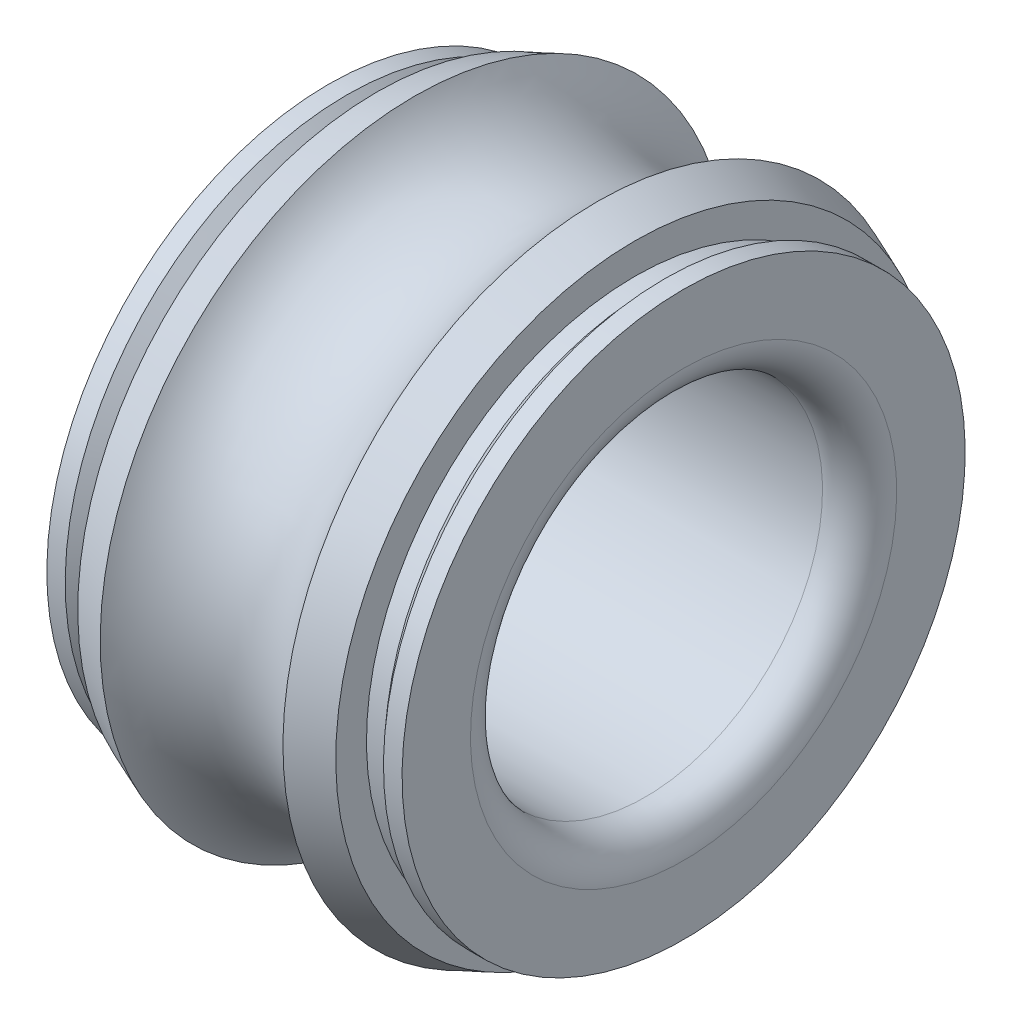
SolidWorks part; units mm, degrees
material "AISI 304"
ref_plane "Plano frontal" through (0, 0, 0) normal (0, 0, 1) x (1, 0, 0)
ref_plane "Plano superior" through (0, 0, 0) normal (0, 1, 0) x (1, 0, 0)
ref_plane "Plano direito" through (0, 0, 0) normal (1, 0, 0) x (0, 0, -1)
sketch "Esboço1" plane through (0, 0, 0) normal (0, 0, 1) x (1, 0, 0)
  line L0 (-22.7175, 2.9568) -> (-17.7175, 2.9568) construction
  line L2 (-1.9877, 2.5015) -> (1.957, 2.5015)
  line L3 (-2.4969, 3.0019) -> (-2.4969, 3.9651)
  line L4 (-1.9705, 8.0015) -> (1.9743, 8.0015)
  line L5 (2.5, 3.0019) -> (2.5, 3.9651)
  line L7 (-2.5, 6.5408) -> (-2.1334, 6.5408)
  line L8 (-1.6236, 6.5408) -> (-1.6236, 6.1298)
  line L9 (-1.6236, 6.1298) -> (-1.1769, 6.1298)
  line L10 (1.6236, 6.1298) -> (1.1769, 6.1298)
  line L11 (1.6236, 6.5408) -> (1.6236, 6.1298)
  line L12 (2.5, 6.5408) -> (2.1334, 6.5408)
  line L13 (-2.1884, 4.1901) -> (-2.1884, 6.0268)
  line L14 (-2.1184, 6.0968) -> (-1.7245, 6.0968)
  line L15 (-1.6545, 6.1668) -> (-1.6545, 6.4667)
  line L16 (-2.1145, 6.4667) -> (-2.1145, 6.3275)
  line L17 (-2.078, 6.2794) -> (-1.8845, 6.2794)
  line L18 (-1.8845, 6.2794) -> (-1.8845, 6.3794)
  line L19 (-1.8845, 6.3794) -> (-1.9445, 6.3794)
  line L20 (-2.0145, 6.4494) -> (-2.0145, 6.4667)
  line L21 (-1.7545, 6.4667) -> (-1.7545, 6.2668)
  line L22 (-1.8245, 6.1968) -> (-2.2192, 6.1968)
  line L23 (-2.1188, 4.1201) -> (-1.9112, 4.1201)
  line L24 (-1.9112, 4.1201) -> (-1.9112, 4.0201)
  line L25 (-1.9112, 4.0201) -> (-2.2184, 4.0201)
  line L26 (-2.2884, 4.0901) -> (-2.2884, 6.0268)
  line L27 (-2.2884, 6.0268) -> (-2.2884, 6.1371)
  line L28 (-2.5, 6.5408) -> (-2.5, 7.5)
  line L29 (2.5, 6.5408) -> (2.5, 7.5)
  line L30 (-2.4969, 3.9651) -> (-2.2384, 3.9651)
  line L31 (-2.2384, 3.9651) -> (-2.0732, 3.7803)
  line L32 (-2.0732, 3.7803) -> (-1.8146, 3.7803)
  line L33 (-1.8146, 3.7803) -> (-1.8146, 4.2124)
  line L34 (-1.8146, 4.2124) -> (-1.2851, 4.4263)
  line L35 (1.8146, 4.2124) -> (1.2851, 4.4263)
  line L36 (1.8146, 3.7803) -> (1.8146, 4.2124)
  line L37 (2.0732, 3.7803) -> (1.8146, 3.7803)
  line L38 (2.2384, 3.9651) -> (2.0732, 3.7803)
  line L39 (2.5, 3.9651) -> (2.2384, 3.9651)
  line L40 (0, 0.0015) -> (-3.7152, 0) construction
  line L41 (0, 0.0015) -> (0, 8) construction
  arc A0 (-2.1334, 6.5408) -> (-1.6236, 6.5408) centre (-1.8785, 6.5408) cw
  arc A1 (-1.2851, 4.4263) -> (1.2851, 4.4263) centre (0, 5.1999) ccw
  arc A2 (2.1334, 6.5408) -> (1.6236, 6.5408) centre (1.8785, 6.5408) ccw
  arc A3 (-2.1884, 6.0268) -> (-2.1184, 6.0968) centre (-2.1184, 6.0268) cw
  arc A4 (-1.6545, 6.4667) -> (-2.1145, 6.4667) centre (-1.8845, 6.4667) ccw
  arc A5 (-2.1145, 6.3275) -> (-2.078, 6.2794) centre (-2.0459, 6.3416) ccw
  arc A6 (-2.0145, 6.4667) -> (-1.7545, 6.4667) centre (-1.8845, 6.4667) cw
  arc A7 (-2.2192, 6.1968) -> (-2.2884, 6.1371) centre (-2.2192, 6.1268) ccw
  arc A8 (1.1769, 6.1298) -> (-1.1769, 6.1298) centre (0, 5.1999) ccw
  arc A9 (-1.9877, 2.5015) -> (-2.4969, 3.0019) centre (-1.9969, 3.0014) cw
  arc A10 (1.957, 2.5015) -> (2.5, 3.0019) centre (2, 2.9996) ccw
  arc A11 (1.9743, 8.0015) -> (2.5, 7.5) centre (2, 7.5021) cw
  arc A12 (-2.5, 7.5) -> (-1.9705, 8.0015) centre (-2, 7.5024) cw
  arc A13 (-2.1884, 4.1901) -> (-2.1188, 4.1201) centre (-2.1184, 4.1901) ccw
  arc A14 (-2.2184, 4.0201) -> (-2.2884, 4.0901) centre (-2.2184, 4.0901) cw
  arc A15 (-1.9445, 6.3794) -> (-2.0145, 6.4494) centre (-1.9445, 6.4494) cw
  arc A16 (-1.7545, 6.2668) -> (-1.8245, 6.1968) centre (-1.8245, 6.2668) cw
  arc A17 (-1.7245, 6.0968) -> (-1.6545, 6.1668) centre (-1.7245, 6.1668) ccw
  point P58 (2.5, 2.75)
  point P61 (2.5, 7.75)
  point P64 (-2.5, 7.75)
  point P82 (2.3692, 3.9651)
  point P106 (-2.0648, 4.0201)
  point P118 (-2.2649, 6.1798)
  point P119 (-2.168, 4.1407)
  point P123 (-2.2679, 4.0406)
  dimension "D4" = 4.0364
  dimension "D9" = 2.5
  dimension "D13" = 1.5
  dimension "D14" = 1.5
  dimension "D15" = 0.5701
  dimension "D16" = 0.4109
  dimension "D17" = 0.5295
  dimension "D21" = 0.2616
  dimension "D18" = 1.2058
  dimension "D35" = 7.0193
  dimension "D39" = 0.2085
  dimension "D40" = 0.3085
  dimension "D41" = 0.4439
  dimension "D42" = 0.3439
  dimension "D43" = 0.8455
  dimension "D6" = 0.3666
  dimension "D31" = 0.5
  dimension "D33" = 4.5
  dimension "D34" = 7.0228
  dimension "D51" = 0.07
  dimension "D52" = 0.07
  dimension "D63" = 0.07
  dimension "D64" = 0.07
  dimension "D72" = 0.3116
  dimension "D1" = 1.4607
  dimension "D2" = 2.5
  dimension "D3" = 8
  dimension "D5" = 5
  dimension "D7" = 1.8717
  dimension "D8" = 1.6236
  dimension "D10" = 1.6236
  dimension "D11" = 2.4969
  dimension "D12" = 2.5
  dimension "D19" = 1.2788
  dimension "D20" = 3.6292
  dimension "D22" = 0.1653
  dimension "D23" = 0.1653
  dimension "D24" = 0.2585
  dimension "D25" = 0.2584
  dimension "D26" = 0.4321
  dimension "D27" = 90
  dimension "D28" = 0.5
  dimension "D29" = 0.9632
  dimension "D30" = 3.9448
  dimension "D32" = 0.9592
  dimension "D36" = 1.5186
  dimension "D37" = 0.5857
  dimension "D38" = 1.6186
  dimension "D44" = 0.6155
  dimension "D45" = 0.23
  dimension "D46" = 0.1
  dimension "D47" = 0.1
  dimension "D48" = 0.1
  dimension "D49" = 0.2614
  dimension "D50" = 0.1935
  dimension "D53" = 0.2999
  dimension "D54" = 0.1999
  dimension "D55" = 0.1392
  dimension "D56" = 0.0173
  dimension "D57" = 0.6339
  dimension "D58" = 0.4173
  dimension "D59" = 0.0482
  dimension "D60" = 0.07
  dimension "D61" = 0.4999
  dimension "D62" = 0.06
  dimension "D65" = 0.3946
  dimension "D66" = 0.0692
  dimension "D67" = 0.1103
  dimension "D68" = 0.5139
  dimension "D69" = 0.3939
  dimension "D70" = 1.8368
  dimension "D71" = 0.2351
  dimension "D73" = 0.2076
  dimension "D74" = 0.07
  dimension "D75" = 0.1206
  dimension "D76" = 0.3567
revolve "Revolução1" add sketch "Esboço1" angle 360 about L40
